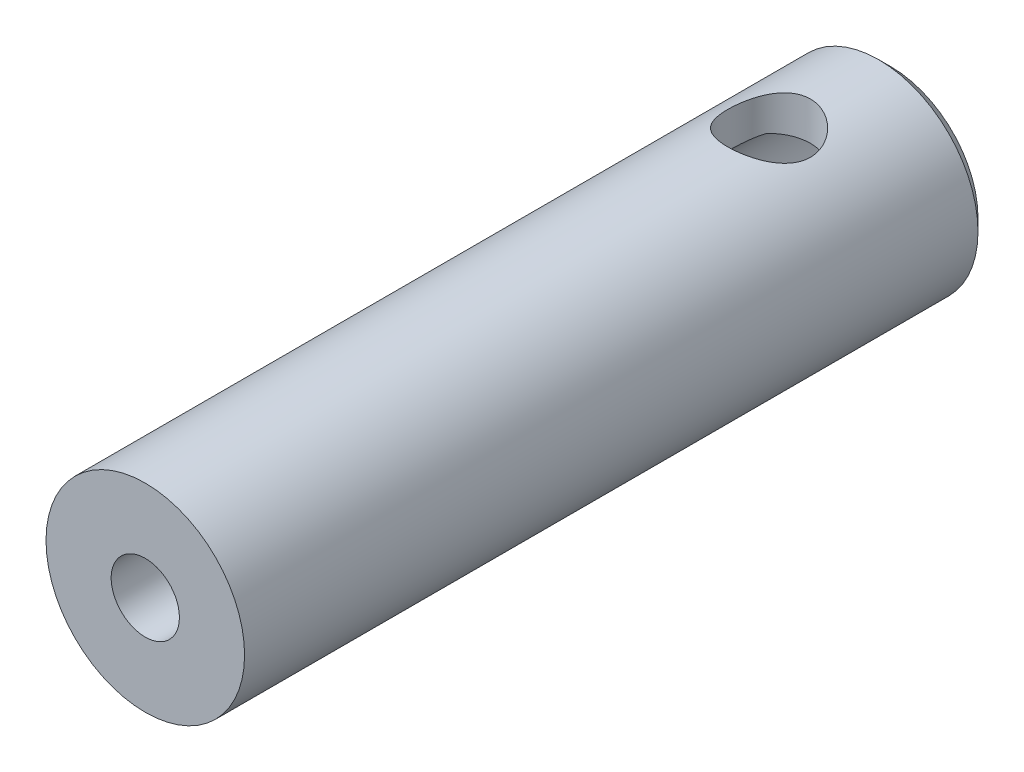
SolidWorks part; units mm, degrees
material "3.0205 (EN-AW 1200)"
ref_plane "Plan de face" through (0, 0, 0) normal (0, 0, 1) x (1, 0, 0)
ref_plane "Plan de dessus" through (0, 0, 0) normal (0, 1, 0) x (1, 0, 0)
ref_plane "Plan de droite" through (0, 0, 0) normal (1, 0, 0) x (0, 0, -1)
sketch "Esquisse1" plane through (0, 0, 0) normal (0, 0, 1) x (1, 0, 0)
  circle A0 centre (0, 0) radius 4.075
  dimension "D1" = 8.15
extrude "Boss.-Extru.1" add sketch "Esquisse1" along normal blind 30.6
sketch "Esquisse2" plane through (0, 0, 0) normal (0, 0, -1) x (-1, 0, 0)
  line L0 (-1.261, 2.5) -> (1.261, 2.5)
  arc A0 (-1.261, 2.5) -> (1.261, 2.5) centre (0, 0) ccw
  dimension "D1" = 2.8
  dimension "D2" = 2.5
extrude "Enlèv. mat.-Extru.1" cut sketch "Esquisse2" against normal blind 14
sketch "Esquisse3" plane through (0, 0, 0) normal (0, 0, -1) x (-1, 0, 0)
  circle A0 centre (0, 0) radius 2.8
extrude "Enlèv. mat.-Extru.2" cut sketch "Esquisse3" against normal blind 3
chamfer "Chanfrein1" distance 0.5 angle 45 1 edges at (4.075, 0, 0)
sketch "Esquisse5" plane through (0, 0, 30.6) normal (0, 0, 1) x (1, 0, 0)
  circle A0 centre (0, 0) radius 1.4
  dimension "D1" = 2.8
extrude "Enlèv. mat.-Extru.4" cut sketch "Esquisse5" against normal blind 10
ref_plane "Plan1" through (0, 4.075, 0) normal (0, 1, 0) x (1, 0, 0)
sketch "Esquisse7" plane through (0, 4.075, 0) normal (0, 1, 0) x (1, 0, 0)
  line L0 (0, 0) -> (0, -5) construction
  point P4 (0, -5)
  dimension "D1" = 5
hole_wizard "Dégagement M31" positions "Esquisse8" profile "Esquisse9" hole size "M3" standard "ISO"
sketch "Esquisse8" plane through (0, 4.075, 0) normal (0, 1, 0) x (1, 0, 0)
  point P0 (0, -5)
sketch "Esquisse9" plane through (0, 4.075, 5) normal (1, 0, 0) x (0, 0, 1)
  line L0 (0, 0) -> (0, 5.0215)
  line L1 (0, 5.0215) -> (1.7, 4)
  line L2 (1.7, 4) -> (1.7, 0)
  line L5 (1.7, 0) -> (0, 0)
  line L10 (0, 5.0215) -> (-1.7, 4) construction
  line L11 (0, -6.35) -> (0, 107.95) construction
  dimension "Diamètre du perçage" = 3.4
  dimension "Profondeur du perçage" = 4
  dimension "Angle de pointe" = 118
sketch "Esquisse10" plane through (0, 0, 0) normal (0, 1, 0) x (1, 0, 0)
  line L0 (4.5892, -26.4508) -> (0, -22.6) construction
  line L2 (0, -22.6) -> (0, -30.6) construction
  line L3 (-4.075, -30.6) -> (4.075, -30.6) construction
  line L4 (2.4223, -23.5882) -> (1.9081, -24.2011)
  line L5 (2.4223, -23.5882) -> (5.1035, -25.838)
  line L7 (1.9081, -24.2011) -> (4.5892, -26.4508)
  line L8 (4.5892, -26.4508) -> (4.075, -27.0637) construction
  line L9 (4.075, -27.0637) -> (1.3938, -24.8139) construction
  line L10 (1.3938, -24.8139) -> (1.9081, -24.2011) construction
  line L11 (4.075, -30.6) -> (4.075, -27.0637) construction
  line L12 (4.5892, -26.4508) -> (5.1035, -25.838)
  dimension "D1" = 0.8
  dimension "D2" = 50
  dimension "D3" = 8
  dimension "D4" = 3.5
revolve "Enlèvement de matière-Révolution1" [suppressed] cut sketch "Esquisse10" angle 360 about L7
pattern_circular "Répétition circulaire1" [suppressed] count 3 over 360
